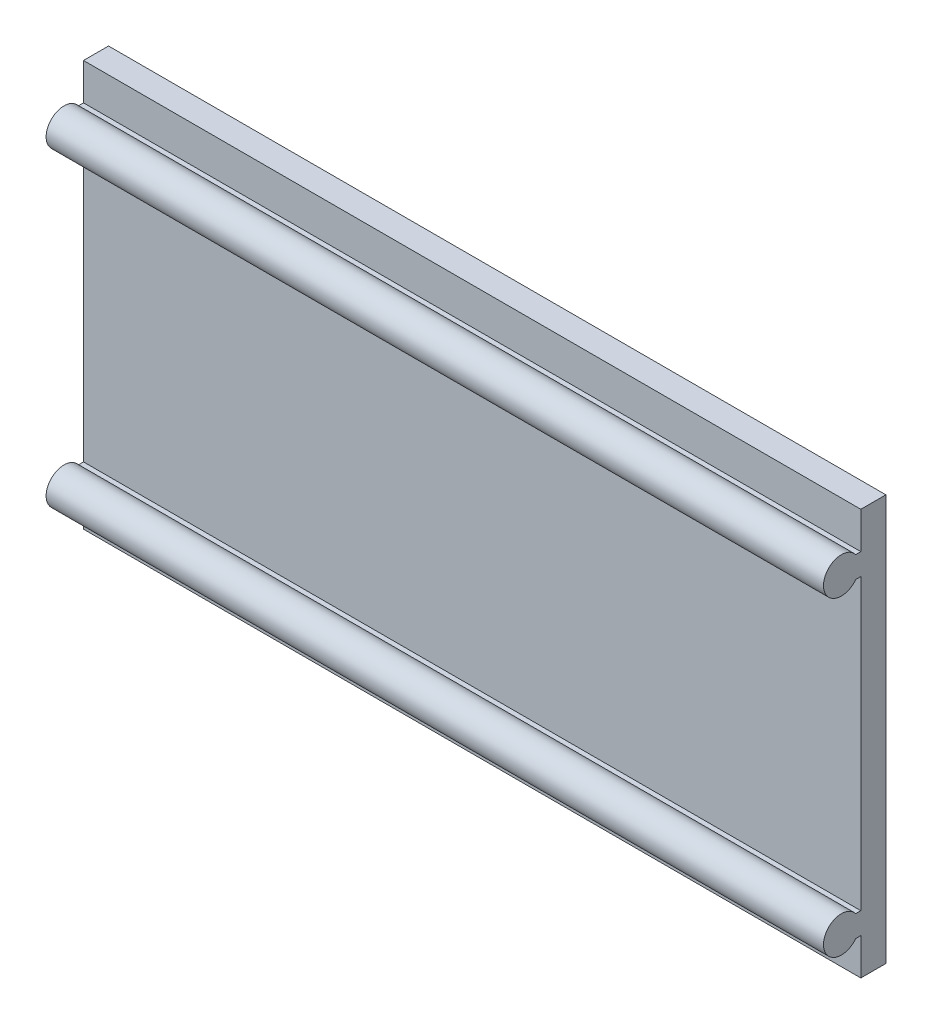
SolidWorks part; units mm, degrees
ref_plane "Спереди" through (0, 0, 0) normal (0, 0, 1) x (1, 0, 0)
ref_plane "Сверху" through (0, 0, 0) normal (0, 1, 0) x (1, 0, 0)
ref_plane "Справа" through (0, 0, 0) normal (1, 0, 0) x (0, 0, -1)
ref_plane "Плоскость4" through (90, 0, 0) normal (1, 0, 0) x (0, 0, -1)
sketch "Эскиз1" plane through (90, 0, 0) normal (1, 0, 0) x (0, 0, -1)
  line L0 (6.75, -24.0938) -> (6.75, 19.25)
  line L1 (6.75, 19.25) -> (-11.5938, 19.25)
  line L2 (-11.5938, 16.75) -> (-11, 16.75)
  line L3 (-11, 16.75) -> (-11, -16.75)
  line L4 (-11, -16.75) -> (-11.5938, -16.75)
  line L5 (-11.5938, -19.25) -> (-11, -19.25)
  line L6 (-11, -19.25) -> (-11, -23.5)
  line L7 (-11, -23.5) -> (-6.75, -23.5)
  line L8 (-6.75, -23.5) -> (-6.75, -24.0938)
  line L9 (-4.25, -24.0938) -> (-4.25, -23.5)
  line L10 (-4.25, -23.5) -> (4.25, -23.5)
  line L11 (4.25, -23.5) -> (4.25, -24.0938)
  arc A0 (-11.5938, 19.25) -> (-11.5938, 16.75) centre (-13.25, 18) ccw
  arc A1 (-11.5938, -16.75) -> (-11.5938, -19.25) centre (-13.25, -18) ccw
  arc A2 (-6.75, -24.0938) -> (-4.25, -24.0938) centre (-5.5, -25.75) ccw
  arc A3 (4.25, -24.0938) -> (6.75, -24.0938) centre (5.5, -25.75) ccw
extrude "Бобышка-Вытянуть1" add sketch "Эскиз1" against normal blind 90
sketch "Эскиз2" plane through (0, 19.25, 0) normal (0, 1, 0) x (-1, 0, 0)
  line L0 (-90, -6.75) -> (-90, 11)
  line L1 (-90, 11) -> (0, 11)
  line L2 (0, 11) -> (0, -6.75)
  line L3 (0, -6.75) -> (-90, -6.75)
extrude "Бобышка-Вытянуть2" add sketch "Эскиз2" along normal blind 8.2
sketch "Эскиз3" plane through (0, 0, -6.75) normal (0, 0, -1) x (-1, 0, 0)
  line L0 (0, -23.5) -> (-90, -23.5)
  line L1 (-90, -23.5) -> (-90, 27.45)
  line L2 (-90, 27.45) -> (0, 27.45)
  line L3 (0, 27.45) -> (0, -23.5)
extrude "Бобышка-Вытянуть3" add sketch "Эскиз3" along normal blind 8.2
sketch "Эскиз4" plane through (0, 0, 0) normal (-1, 0, 0) x (0, 0, 1)
  line L0 (-14.95, -14.75) -> (-11, -14.75)
  line L1 (-11, -14.75) -> (-11, 14.75)
  line L2 (-11, 14.75) -> (-14.95, 14.75)
  line L3 (-14.95, 14.75) -> (-14.95, -14.75)
extrude "Вырез-Вытянуть1" cut sketch "Эскиз4" against normal through all
sketch "Эскиз5" plane through (0, 0, 0) normal (-1, 0, 0) x (0, 0, 1)
  line L0 (-14.95, 27.45) -> (-14.95, 21.25)
  line L1 (-14.95, 21.25) -> (-11, 21.25)
  line L2 (-11, 21.25) -> (-11, 27.45)
  line L3 (-11, 27.45) -> (-14.95, 27.45)
extrude "Вырез-Вытянуть2" cut sketch "Эскиз5" against normal through all
sketch "Эскиз6" plane through (0, 0, 0) normal (-1, 0, 0) x (0, 0, 1)
  line L0 (-11, 27.45) -> (-11, 23.5)
  line L1 (-11, 23.5) -> (-8.75, 23.5)
  line L2 (-8.75, 23.5) -> (-8.75, 27.45)
  line L3 (-8.75, 27.45) -> (-11, 27.45)
extrude "Вырез-Вытянуть3" cut sketch "Эскиз6" against normal through all
sketch "Эскиз7" plane through (0, 0, 0) normal (-1, 0, 0) x (0, 0, 1)
  line L0 (-2.25, 27.45) -> (-2.25, 23.5)
  line L1 (-2.25, 23.5) -> (2.25, 23.5)
  line L2 (2.25, 23.5) -> (2.25, 27.45)
  line L3 (2.25, 27.45) -> (-2.25, 27.45)
extrude "Вырез-Вытянуть4" cut sketch "Эскиз7" against normal through all
sketch "Эскиз8" plane through (0, 0, 0) normal (-1, 0, 0) x (0, 0, 1)
  line L0 (11, 27.45) -> (8.75, 27.45)
  line L1 (8.75, 27.45) -> (8.75, 23.5)
  line L2 (8.75, 23.5) -> (11, 23.5)
  line L3 (11, 23.5) -> (11, 27.45)
extrude "Вырез-Вытянуть5" cut sketch "Эскиз8" against normal through all
sketch "Эскиз9" plane through (0, 0, 0) normal (-1, 0, 0) x (0, 0, 1)
  line L0 (-14.95, -23.5) -> (-11, -23.5)
  line L1 (-11, -23.5) -> (-11, -21.25)
  line L2 (-11, -21.25) -> (-14.95, -21.25)
  line L3 (-14.95, -21.25) -> (-14.95, -23.5)
extrude "Вырез-Вытянуть6" cut sketch "Эскиз9" against normal through all
sketch "Эскиз10" plane through (90, 0, 0) normal (1, 0, 0) x (0, 0, -1)
  line L0 (10.1, 22.6) -> (-10.1, 22.6)
  line L1 (-10.1, 22.6) -> (-10.1, -22.6)
  line L2 (-10.1, -22.6) -> (10.1, -22.6)
  line L3 (10.1, -22.6) -> (10.1, 22.6)
extrude "Вырез-Вытянуть7" cut sketch "Эскиз10" against normal blind 86
hole_wizard "Диаметр отверстия Ø2.5 (2.5)1" positions "Эскиз12" profile "Эскиз11" hole size "Ø2.5" standard "Ansi Metric"
sketch "Эскиз12" plane through (90, 0, 0) normal (1, 0, 0) x (0, 0, -1)
  point P0 (5.5, -25.75)
  point P1 (-13.25, -18)
  point P2 (-5.5, -25.75)
  point P3 (-13.25, 18)
sketch "Эскиз11" plane through (90, -25.75, -5.5) normal (0, 1, 0) x (0, 0, -1)
  line L0 (0, 0) -> (0, 90)
  line L1 (0, 90) -> (1.25, 90)
  line L2 (1.25, 90) -> (1.25, 0)
  line L5 (1.25, 0) -> (0, 0)
  line L11 (0, -6.35) -> (0, 107.95) construction
  dimension "Диаметр сквозного отверстия" = 2.5
  dimension "Глубина сквозного отверстия" = 90
hole_wizard "Диаметр отверстия Ø4.5 (4.5)1" positions "Эскиз14" profile "Эскиз13" hole size "Ø4.5" standard "Ansi Metric"
sketch "Эскиз14" plane through (0, 0, 0) normal (-1, 0, 0) x (0, 0, 1)
  point P0 (-13.25, -18)
  point P1 (-13.25, 18)
  point P2 (-5.5, 25.75)
  point P3 (5.5, 25.75)
sketch "Эскиз13" plane through (0, -18, -13.25) normal (0, 1, 0) x (0, 0, 1)
  line L0 (0, 0) -> (0, 90)
  line L1 (0, 90) -> (2.25, 90)
  line L2 (2.25, 90) -> (2.25, 0)
  line L5 (2.25, 0) -> (0, 0)
  line L11 (0, -6.35) -> (0, 107.95) construction
  dimension "Диаметр сквозного отверстия" = 4.5
  dimension "Глубина сквозного отверстия" = 90
hole_wizard "Диаметр отверстия Ø8.3 (8.3)1" positions "Эскиз16" profile "Эскиз15" hole size "Ø8.3" standard "Ansi Metric"
sketch "Эскиз16" plane through (0, 0, 0) normal (-1, 0, 0) x (0, 0, 1)
  point P0 (0, 0)
sketch "Эскиз15" plane through (0, 0, 0) normal (0, 1, 0) x (0, 0, 1)
  line L0 (0, 0) -> (0, 3.2)
  line L1 (0, 3.2) -> (4.15, 3.2)
  line L2 (4.15, 3.2) -> (4.15, 0)
  line L5 (4.15, 0) -> (0, 0)
  line L10 (0, 3.2) -> (-4.15, 3.2) construction
  line L11 (0, -6.35) -> (0, 107.95) construction
  dimension "Диаметр отверстия" = 8.3
  dimension "Глубина отверстия" = 3.2
  dimension "Угол заточки сверла" = 180
fillet "Скругление1" radius 2 1 edges at (45, 23.5, 8.75)
fillet "Скругление2" radius 2 11 edges at (4, -22.6, 0) (4, 0, -10.1) (4, 0, 10.1) (4, 22.6, 0) (45, -21.25, -11) (45, -14.75, -11) (45, 14.75, -11) (45, 21.25, -11) (45, 23.5, -8.75) (45, 23.5, -2.25) (45, 23.5, 2.25)
sketch "Эскиз17" plane through (90, 0, 0) normal (1, 0, 0) x (0, 0, -1)
  circle A0 centre (5.5, -25.75) radius 1.25 construction
  circle A1 centre (-5.5, -25.75) radius 1.25 construction
  circle A2 centre (-13.25, -18) radius 1.25 construction
  circle A3 centre (-13.25, 18) radius 1.25 construction
  circle A4 centre (5.5, -25.75) radius 1.25
  circle A5 centre (-5.5, -25.75) radius 1.25
  circle A6 centre (-13.25, -18) radius 1.25
  circle A7 centre (-13.25, 18) radius 1.25
extrude "Бобышка-Вытянуть4" add sketch "Эскиз17" against normal blind 90
sketch "Эскиз18" plane through (0, 0, 0) normal (-1, 0, 0) x (0, 0, 1)
  circle A0 centre (0, 0) radius 4.15 construction
  circle A1 centre (0, 0) radius 4.15
extrude "Вырез-Вытянуть8" cut sketch "Эскиз18" against normal blind 100
sketch "Эскиз19" plane through (90, 0, 0) normal (1, 0, 0) x (0, 0, -1)
  line L1 (-10.1, -22.6) -> (-10.1, 22.6) construction
  line L2 (-10.1, -22.6) -> (-10.1, 22.6)
  line L7 (-10.1, 22.6) -> (-10.1, 31.781)
  line L8 (-10.1, 31.781) -> (18.1176, 31.781)
  line L9 (18.1176, 31.781) -> (18.667, -30.7697)
  line L10 (18.667, -30.7697) -> (-10.1, -30.7697)
  line L11 (-10.1, -30.7697) -> (-10.1, -22.6)
extrude "Вырез-Вытянуть11" cut sketch "Эскиз19" against normal blind 108
sketch "Эскиз20" plane through (90, 0, 0) normal (1, 0, 0) x (0, 0, -1)
  line L0 (-10.75, 23.5) -> (-10.1, 23.5)
  line L1 (-10.1, 23.6086) -> (-10.1, -23.5) construction
  line L2 (-10.1, 23.6086) -> (-10.1, 23.5)
  arc A0 (-10.75, 23.5) -> (-10.1, 23.6086) centre (-10.75, 25.5) ccw construction
  arc A1 (-10.75, 23.5) -> (-10.1, 23.6086) centre (-10.75, 25.5) ccw
extrude "Вырез-Вытянуть12" cut sketch "Эскиз20" against normal blind 108
sketch "Эскиз21" plane through (0, 0, 10.1) normal (0, 0, -1) x (-1, 0, 0)
  line L4 (0, -23.5) -> (0, 23.5)
  line L5 (0, 23.5) -> (-90, 23.5)
  line L6 (-90, 23.5) -> (-90, -23.5)
  line L7 (-90, -23.5) -> (0, -23.5)
  line L8 (0, -23.5) -> (0, 23.5)
  line L9 (0, 23.5) -> (-90, 23.5)
  line L10 (-90, 23.5) -> (-90, -23.5)
  line L11 (-90, -23.5) -> (0, -23.5)
  dimension "D1" = 0
extrude "Бобышка-Вытянуть5" add sketch "Эскиз21" along normal blind 2
